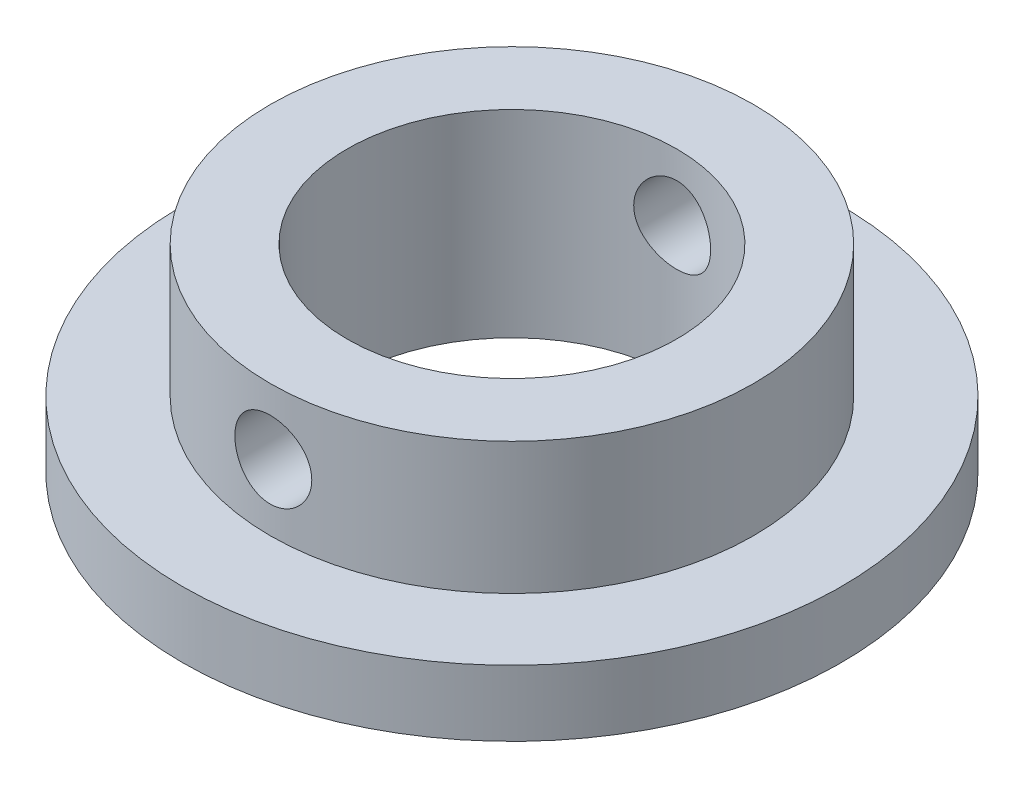
SolidWorks part; units mm, degrees
ref_plane "Front Plane" through (0, 0, 0) normal (0, 0, 1) x (1, 0, 0)
ref_plane "Top Plane" through (0, 0, 0) normal (0, 1, 0) x (1, 0, 0)
ref_plane "Right Plane" through (0, 0, 0) normal (1, 0, 0) x (0, 0, -1)
sketch "Sketch1" plane through (0, 0, 0) normal (0, 1, 0) x (1, 0, 0)
  circle A0 centre (0, 0) radius 15
  circle A1 centre (0, 0) radius 7.5
  dimension "D1" = 15
  dimension "D2" = 30
extrude "Boss-Extrude1" add sketch "Sketch1" along normal blind 3
sketch "Sketch2" plane through (0, 3, 0) normal (0, 1, 0) x (1, 0, 0)
  circle A0 centre (0, 0) radius 11
  circle A1 centre (0, 0) radius 7.5
  dimension "D1" = 22
  dimension "D2" = 15
extrude "Boss-Extrude2" add sketch "Sketch2" along normal blind 6
sketch "Sketch3" plane through (0, 0, 0) normal (0, 0, 1) x (1, 0, 0)
  line L0 (11, 9) -> (-11, 9) construction
  circle A0 centre (0, 6) radius 1.75
  dimension "D1" = 3.5
  dimension "D2" = 3
extrude "Cut-Extrude1" cut sketch "Sketch3" against normal through all both and the other way through all
